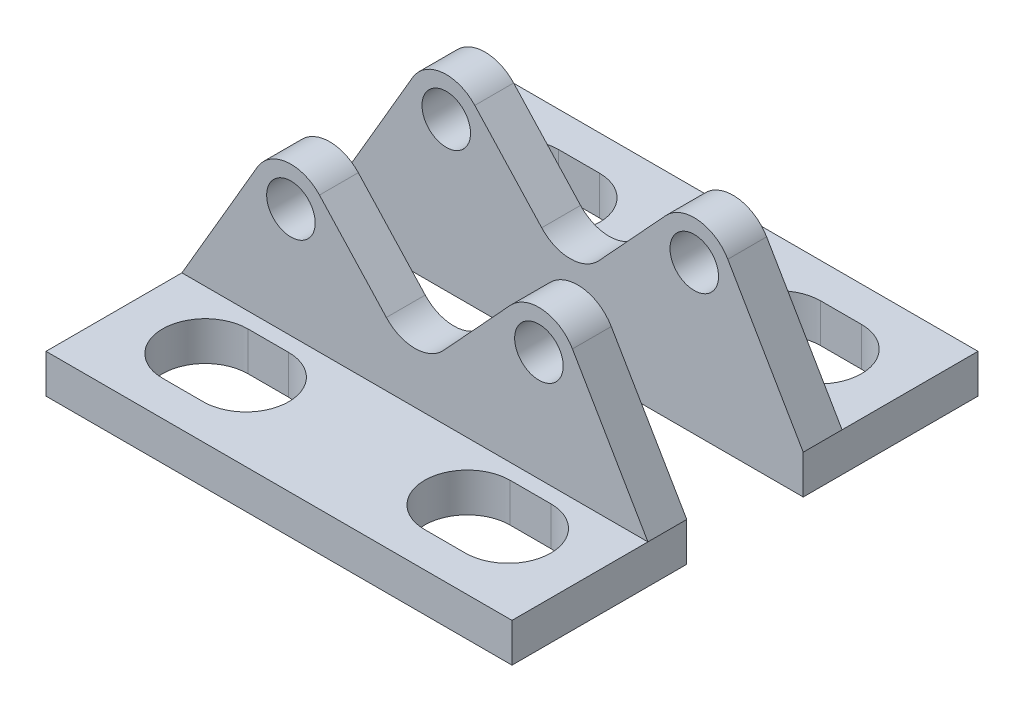
SolidWorks part; units mm, degrees
ref_plane "Front Plane" through (0, 0, 0) normal (0, 0, 1) x (1, 0, 0)
ref_plane "Top Plane" through (0, 0, 0) normal (0, 1, 0) x (1, 0, 0)
ref_plane "Right Plane" through (0, 0, 0) normal (1, 0, 0) x (0, 0, -1)
sketch "Sketch3" plane through (0, 0, 0) normal (0, 1, 0) x (1, 0, 0)
  line L3 (-12, -12) -> (12, -12)
  line L5 (-12, 12) -> (12, -12) construction
  line L6 (-12, -12) -> (12, 12) construction
  line L14 (-12, -12) -> (-12, -5)
  line L15 (-12, -5) -> (12, -5)
  line L16 (12, -5) -> (12, -12)
  line L17 (-10.8689, 0) -> (13.5472, 0) construction
  line L18 (12, 5) -> (12, 12)
  line L19 (-12, 5) -> (12, 5)
  line L20 (-12, 12) -> (-12, 5)
  line L21 (-12, 12) -> (12, 12)
  point P0 (0, 0)
  dimension "D1" = 10
  dimension "D2" = 24
extrude "Boss-Extrude2" add sketch "Sketch3" along normal blind 2
sketch "Sketch4" plane through (0, 2, 0) normal (0, 1, 0) x (1, 0, 0)
  line L0 (-7.8, -8) -> (-5.7, -8) construction
  line L3 (5.7, -8) -> (7.8, -8) construction
  line L4 (-12, -8) -> (12, -8) construction
  line L6 (-7.8, -5.8) -> (-5.7, -5.8)
  line L7 (-7.8, -10.2) -> (-5.7, -10.2)
  line L9 (-7.8, 8) -> (-5.7, 8) construction
  line L12 (5.7, -10.2) -> (7.8, -10.2)
  line L13 (5.7, -5.8) -> (7.8, -5.8)
  line L14 (-3.3738, 0) -> (4.3427, 0) construction
  line L15 (-7.8, 5.8) -> (-5.7, 5.8)
  line L16 (-7.8, 10.2) -> (-5.7, 10.2)
  line L17 (5.7, 8) -> (7.8, 8) construction
  line L18 (5.7, 10.2) -> (7.8, 10.2)
  line L19 (5.7, 5.8) -> (7.8, 5.8)
  arc A2 (-7.8, -5.8) -> (-7.8, -10.2) centre (-7.8, -8) ccw
  arc A3 (-5.7, -10.2) -> (-5.7, -5.8) centre (-5.7, -8) ccw
  arc A6 (5.7, -10.2) -> (5.7, -5.8) centre (5.7, -8) cw
  arc A7 (7.8, -5.8) -> (7.8, -10.2) centre (7.8, -8) cw
  arc A8 (-7.8, 5.8) -> (-7.8, 10.2) centre (-7.8, 8) cw
  arc A9 (-5.7, 10.2) -> (-5.7, 5.8) centre (-5.7, 8) cw
  arc A10 (5.7, 10.2) -> (5.7, 5.8) centre (5.7, 8) ccw
  arc A11 (7.8, 5.8) -> (7.8, 10.2) centre (7.8, 8) ccw
  point P2 (-6.75, -8)
  point P16 (-6.75, 8)
  point P23 (6.75, -8)
  point P33 (6.75, 8)
  dimension "D1" = 16
  dimension "D2" = 16
  dimension "D3" = 2.2
sketch "Sketch5" plane through (0, 0, 5) normal (0, 0, -1) x (-1, 0, 0)
  line L3 (-12, 2) -> (-6.75, 11)
  line L4 (-6.75, 11) -> (0, 3.6796)
  line L7 (-12, 2) -> (12, 2) construction
  line L8 (-12, 2) -> (-12, 0)
  line L9 (6.75, 11) -> (0, 3.6796)
  line L10 (12, 2) -> (6.75, 11)
  line L12 (-12, 0) -> (12, 0)
  line L13 (12, 0) -> (12, 2)
  point P0 (0, 3.6796)
  dimension "D1" = 9
sketch "Sketch6" plane through (0, 0, 0) normal (0, 1, 0) x (1, 0, 0)
  line L0 (9.1872, 0) -> (-7.8723, 0) construction
extrude "Boss-Extrude3" add sketch "Sketch5" along normal blind 2
fillet "Fillet3" radius 2 3 edges at (6.75, 11, 4) (-6.75, 11, 4) (0, 3.6796, 4)
extrude "Cut-Extrude2" cut sketch "Sketch4" against normal blind 2
mirror "Mirror34" about plane through (0, 0, 0) normal (0, 0, 1) of "Boss-Extrude2", "Boss-Extrude3", "Fillet3", "Cut-Extrude2"
sketch "Sketch7" plane through (0, 0, 5) normal (0, 0, 1) x (1, 0, 0)
  line L0 (0, 0) -> (0, 5.1847) construction
  circle A3 centre (-6.3859, 7.6548) radius 1.25
  circle A4 centre (6.3859, 7.6548) radius 1.25
extrude "Cut-Extrude3" cut sketch "Sketch7" against normal through all both and the other way through all
